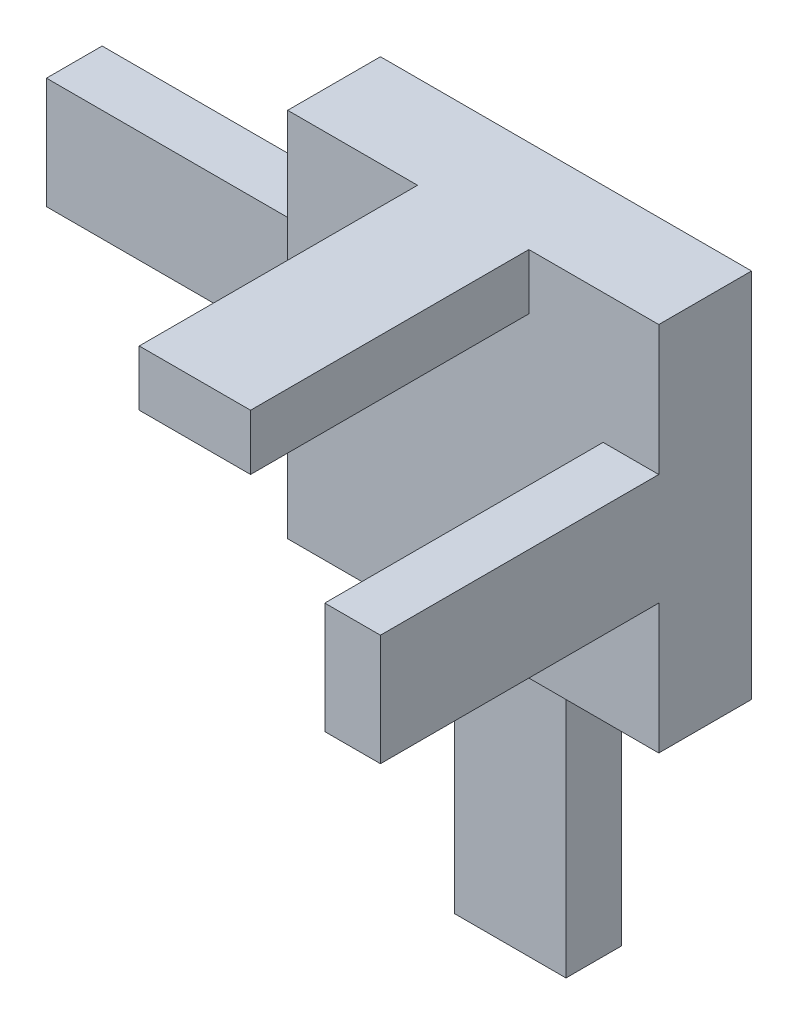
SolidWorks part; units mm, degrees
ref_plane "Спереди" through (0, 0, 0) normal (0, 0, 1) x (1, 0, 0)
ref_plane "Сверху" through (0, 0, 0) normal (0, 1, 0) x (1, 0, 0)
ref_plane "Справа" through (0, 0, 0) normal (1, 0, 0) x (0, 0, -1)
sketch "Эскиз1" plane through (0, 0, 0) normal (0, 0, 1) x (1, 0, 0)
  line L1 (0, 0) -> (20, 0)
  line L2 (0, 0) -> (0, 20)
  line L3 (0, 20) -> (20, 20)
  line L4 (20, 0) -> (20, 20)
  dimension "D1" = 20
  dimension "D2" = 20
extrude "Бобышка-Вытянуть1" add sketch "Эскиз1" along normal blind 5
sketch "Эскиз2" plane through (0, 0, 5) normal (0, 0, 1) x (1, 0, 0)
  line L0 (20, 20) -> (0, 20) construction
  line L1 (7, 20) -> (13, 20)
  line L2 (7, 20) -> (7, 17)
  line L3 (7, 17) -> (13, 17)
  line L4 (13, 20) -> (13, 17)
  line L5 (20, 0) -> (20, 20) construction
  line L6 (20, 13) -> (17, 13)
  line L7 (20, 13) -> (20, 7)
  line L8 (20, 7) -> (17, 7)
  line L9 (17, 13) -> (17, 7)
  line L10 (20, 0) -> (20, 20) construction
  line L11 (20, 20) -> (0, 20) construction
  point P12 (20, 10)
  point P15 (20, 10)
  point P16 (10, 20)
  point P19 (10, 20)
  dimension "D1" = 6
  dimension "D2" = 6
  dimension "D3" = 3
  dimension "D4" = 3
extrude "Бобышка-Вытянуть2" add sketch "Эскиз2" along normal blind 15
sketch "Эскиз3" plane through (0, 0, 0) normal (0, -1, 0) x (1, 0, 0)
  line L0 (0, 0) -> (20, 0) construction
  line L1 (7, 0) -> (13, 0)
  line L2 (7, 0) -> (7, 3)
  line L3 (7, 3) -> (13, 3)
  line L4 (13, 0) -> (13, 3)
  line L5 (0, 5) -> (20, 5) construction
  point P6 (10, 0)
  point P9 (10, 5)
  dimension "D1" = 6
  dimension "D2" = 3
extrude "Бобышка-Вытянуть3" add sketch "Эскиз3" along normal blind 15
sketch "Эскиз4" plane through (0, 0, 0) normal (-1, 0, 0) x (0, 0, 1)
  line L0 (0, 20) -> (0, 0) construction
  line L1 (0, 13) -> (3, 13)
  line L2 (0, 13) -> (0, 7)
  line L3 (0, 7) -> (3, 7)
  line L4 (3, 13) -> (3, 7)
  line L5 (5, 20) -> (5, 0) construction
  point P6 (0, 10)
  point P9 (5, 10)
  dimension "D1" = 3
  dimension "D2" = 6
extrude "Бобышка-Вытянуть4" add sketch "Эскиз4" along normal blind 15
